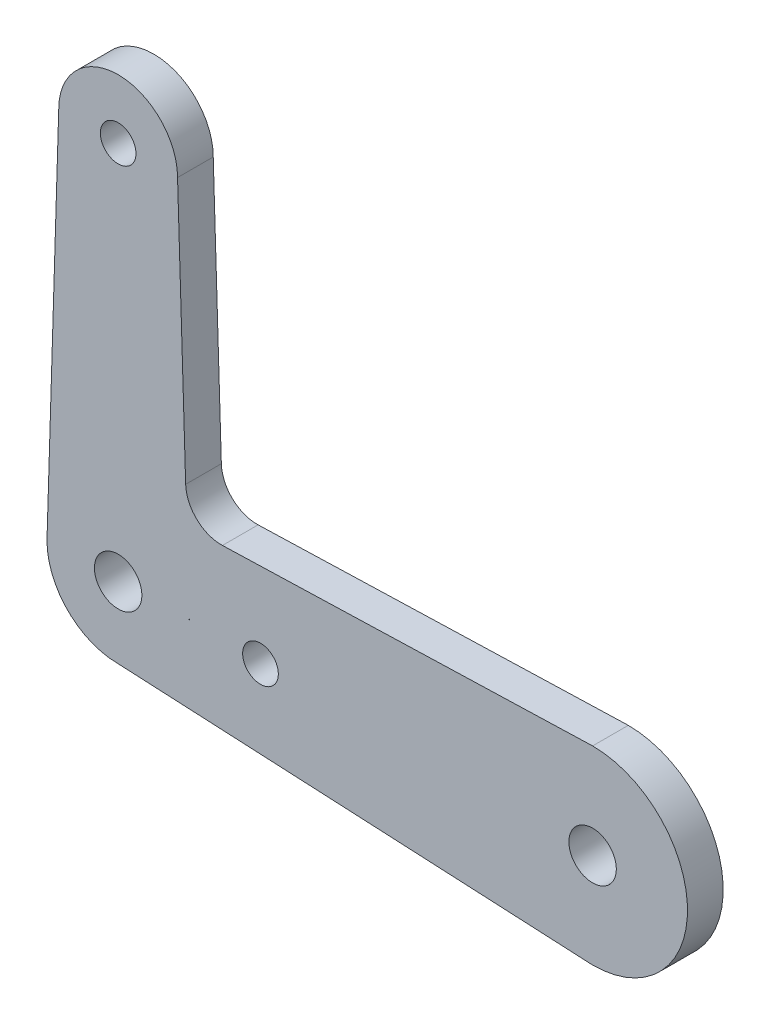
SolidWorks part; units mm, degrees
ref_plane "Front Plane" through (0, 0, 0) normal (0, 0, 1) x (1, 0, 0)
ref_plane "Top Plane" through (0, 0, 0) normal (0, 1, 0) x (1, 0, 0)
ref_plane "Right Plane" through (0, 0, 0) normal (1, 0, 0) x (0, 0, -1)
sketch "Sketch1" plane through (0, 0, 0) normal (0, 0, 1) x (1, 0, 0)
  line L0 (-7.9502, 50.8) -> (-9.525, 0)
  line L1 (9.525, 0) -> (9.5067, 0.59)
  line L2 (0, -9.525) -> (63.5, -12.7)
  line L3 (63.5, 12.7) -> (9.1835, 11.0162)
  line L4 (9.1835, 11.0162) -> (7.9502, 50.8)
  arc A0 (-9.5067, 0.59) -> (0, -9.525) centre (0, 0) ccw
  arc A1 (7.9502, 50.8) -> (-7.9502, 50.8) centre (0, 50.8) ccw
  arc A2 (62.2332, -12.6367) -> (62.7134, 12.6756) centre (63.5, 0) ccw
  arc A3 (9.525, 0) -> (9.5067, 0.59) centre (0, 0) ccw
  dimension "D1" = 19.05
  dimension "D2" = 15.9004
  dimension "D3" = 25.4
  dimension "D4" = 50.8
  dimension "D5" = 63.5
extrude "Boss-Extrude1" add sketch "Sketch1" along normal blind 4.7752 contours L2 A2 L3 L4 A1 L0 A0 A3 L1
sketch "Sketch2" plane through (0, 0, 4.7752) normal (0, 0, 1) x (1, 0, 0)
  circle A0 centre (0, 0) radius 3.175
  circle A1 centre (0, 50.8) radius 2.3876
  circle A2 centre (19.05, 0) radius 2.3876
  circle A3 centre (63.5, 0) radius 3.175
  arc A4 (7.9502, 50.8) -> (-7.9502, 50.8) centre (0, 50.8) ccw construction
  arc A9 (63.5, -12.7) -> (63.5, 12.7) centre (63.5, 0) ccw construction
  point P9 (0, 51.741)
  point P13 (0, 0)
  dimension "D1" = 4.7752
  dimension "D2" = 6.35
  dimension "D3" = 4.7752
  dimension "D4" = 6.35
  dimension "D8" = 50.8
  dimension "D5" = 44.45
  dimension "D6" = 19.05
  dimension "D7" = 0
fillet "Fillet1" radius 4.7752 1 edges at (9.1835, 11.0162, 2.3876)
extrude "Cut-Extrude1" cut sketch "Sketch2" against normal blind 4.7752
